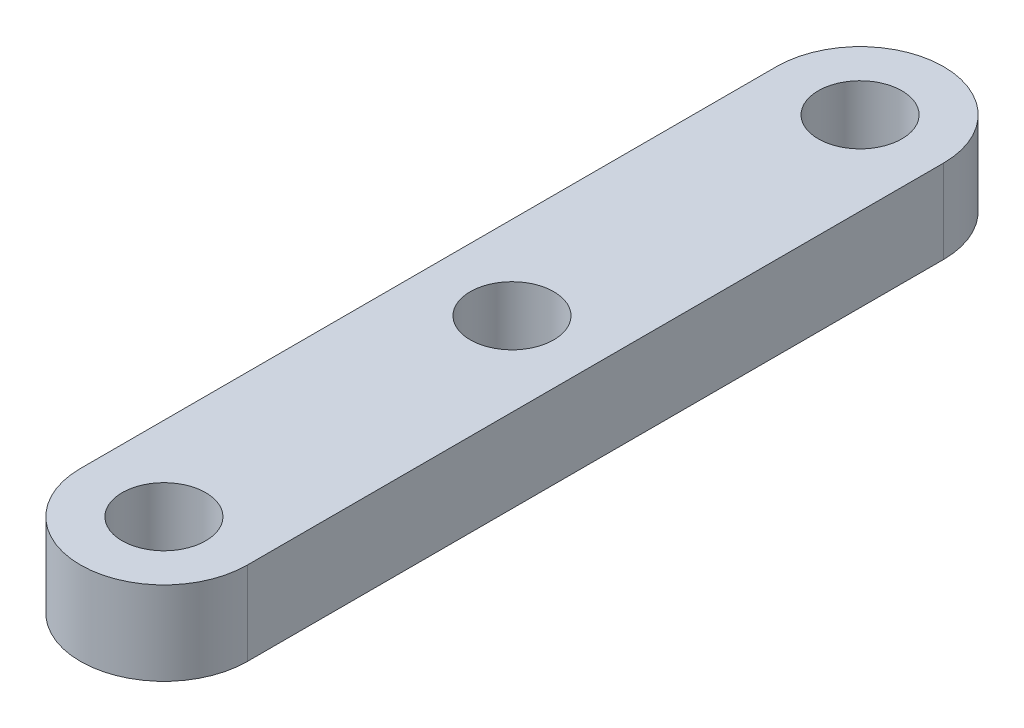
SolidWorks part; units mm, degrees
ref_plane "Front Plane" through (0, 0, 0) normal (0, 0, 1) x (1, 0, 0)
ref_plane "Top Plane" through (0, 0, 0) normal (0, 1, 0) x (1, 0, 0)
ref_plane "Right Plane" through (0, 0, 0) normal (1, 0, 0) x (0, 0, -1)
sketch "Sketch2" plane through (0, 0, 0) normal (0, 1, 0) x (1, 0, 0)
  line L0 (0, -12.5) -> (0, 12.5)
  line L1 (0, -12.5) -> (-25, -12.5)
  line L2 (0, 12.5) -> (25, 12.5)
  line L3 (0, 0) -> (-12.4066, 38.0273)
  line L4 (-12.4066, 38.0273) -> (-32, 22.5)
  line L5 (-32, 22.5) -> (-52.7065, 30.7)
  line L6 (-52.7065, 30.7) -> (-30.6151, 86.485)
  line L7 (-12, 27.5) -> (-10.6151, 91.485)
  line L8 (-32, 22.5) -> (-30.6151, 86.485) construction
  line L9 (-10.6151, 91.485) -> (-30.6151, 86.485)
  line L10 (0, -57.9364) -> (0, 57.9364) construction
  line L11 (0, 0) -> (12.4066, 38.0273)
  line L12 (32, 22.5) -> (30.6151, 86.485) construction
  line L13 (10.6151, 91.485) -> (30.6151, 86.485)
  line L14 (12, 27.5) -> (10.6151, 91.485)
  line L15 (52.7065, 30.7) -> (30.6151, 86.485)
  line L16 (32, 22.5) -> (52.7065, 30.7)
  line L17 (12.4066, 38.0273) -> (32, 22.5)
  line L18 (-25, -6.5) -> (-25, -46.5) construction
  line L19 (-15, -6.5) -> (-35, -6.5)
  line L20 (-15, -6.5) -> (-15, -46.5)
  line L21 (-15, -46.5) -> (-35, -46.5)
  line L22 (-35, -6.5) -> (-35, -46.5)
  circle A0 centre (25, 12.5) radius 1.5
  circle A1 centre (-25, -12.5) radius 1.5
  circle A2 centre (-12, 27.5) radius 1.5
  circle A3 centre (-32, 22.5) radius 1.5
  circle A4 centre (32, 22.5) radius 1.5
  circle A5 centre (12, 27.5) radius 1.5
  circle A6 centre (-25, -12.5) radius 9.2314
  point P15 (0, 0)
  dimension "D3" = 3
  dimension "D1" = 25
  dimension "D2" = 25
  dimension "D5" = 12.5
  dimension "D4" = 12.5
  dimension "D6" = 25
  dimension "D7" = 25
  dimension "D8" = 40
  dimension "D10" = 25
  dimension "D11" = 120
  dimension "D15" = 20
  dimension "D17" = 40
  dimension "D9" = 12
  dimension "D14" = 5
  dimension "D13" = 64
  dimension "D12" = 60
  dimension "D16" = 40
  dimension "D18" = 20
  dimension "D19" = 6
sketch "Sketch3" plane through (0, 0, 0) normal (0, 1, 0) x (1, 0, 0)
  line L1 (0, 12.5) -> (0, -12.5) construction
  line L2 (-3, 12.5) -> (-3, -12.5)
  line L3 (3, 12.5) -> (3, -12.5)
  arc A0 (-3, 12.5) -> (3, 12.5) centre (0, 12.5) cw
  arc A1 (-3, -12.5) -> (3, -12.5) centre (0, -12.5) ccw
  circle A2 centre (0, 12.5) radius 1.5
  circle A3 centre (0, 0) radius 1.5
  circle A4 centre (0, -12.5) radius 1.5
  dimension "D3" = 3
  dimension "D1" = 3
  dimension "D2" = 3
extrude "Boss-Extrude1" add sketch "Sketch3" along normal blind 3
equation "\"a\"= \"b\" / 2"
equation "\"b\"= 25"
equation "\"D1@Sketch2\"=2*\"a\""
equation "\"D2@Sketch2\"=\"b\""
equation "\"D5@Sketch2\"=\"a\""
equation "\"D4@Sketch2\"=\"a\""
equation "\"D6@Sketch2\"=\"b\""
equation "\"D7@Sketch2\"=\"b\""
equation "\"c\"= 64"
equation "\"D13@Sketch2\"=\"c\""
equation "\"D12@Sketch2\"=\"c\"-4"
